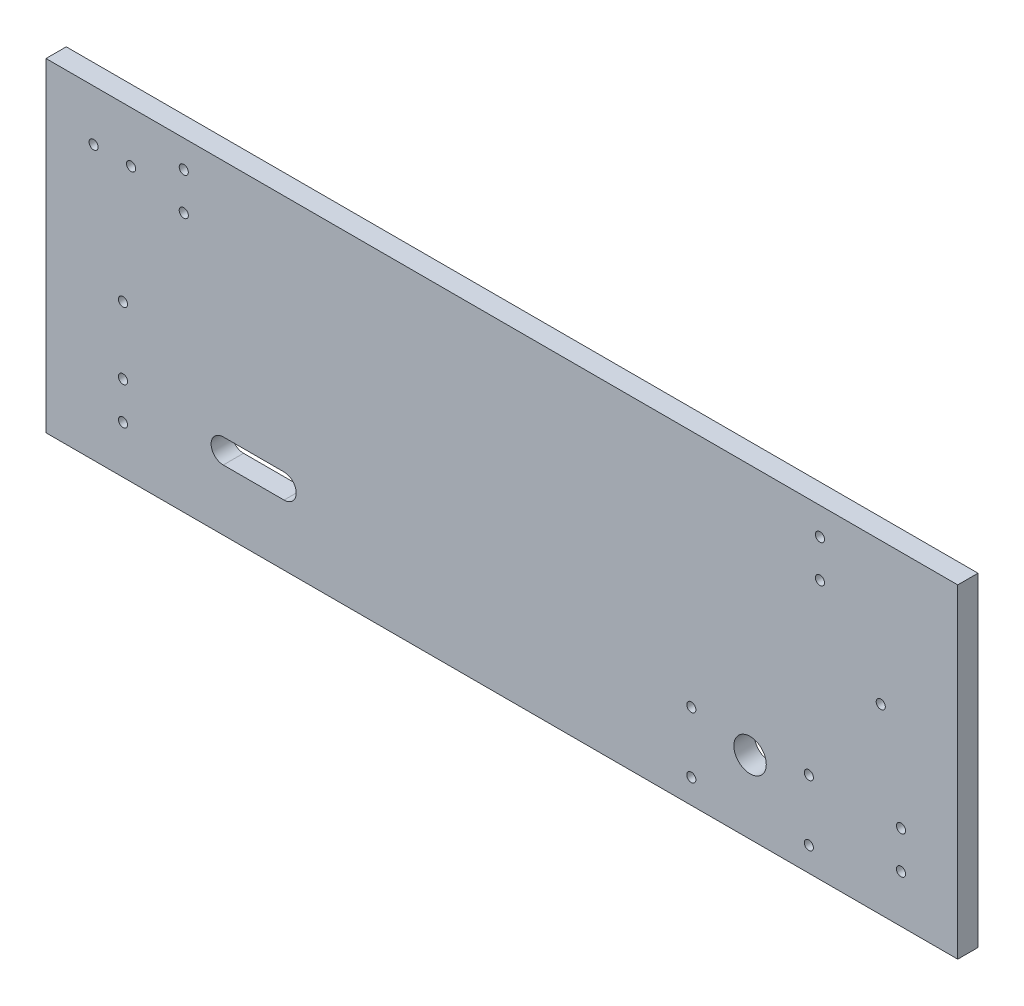
SolidWorks part; units mm, degrees
material "Pino"
ref_plane "Piano frontale" through (0, 0, 0) normal (0, 0, 1) x (1, 0, 0)
ref_plane "Piano superiore" through (0, 0, 0) normal (0, 1, 0) x (1, 0, 0)
ref_plane "Piano destro" through (0, 0, 0) normal (1, 0, 0) x (0, 0, -1)
sketch "Schizzo1" plane through (0, 0, 0) normal (0, 0, 1) x (1, 0, 0)
  line L1 (0, 0) -> (450, 0)
  line L2 (0, 0) -> (0, 160)
  line L3 (0, 160) -> (450, 160)
  line L4 (450, 0) -> (450, 160)
  dimension "D1" = 450
  dimension "D2" = 160
extrude "Estrusione-Estrusione1" add sketch "Schizzo1" along normal blind 10
sketch "Schizzo2" plane through (0, 0, 10) normal (0, 0, 1) x (1, 0, 0)
  line L0 (102.5, 36) -> (347.5, 36) construction
  line L1 (225, 0) -> (225, 36) construction
  line L2 (0, 0) -> (450, 0) construction
  line L3 (87.5, 36) -> (117.5, 36) construction
  line L4 (87.5, 42) -> (117.5, 42)
  line L5 (87.5, 30) -> (117.5, 30)
  line L7 (376.5, 42) -> (318.5, 42) construction
  line L8 (376.5, 42) -> (376.5, 12) construction
  line L9 (376.5, 12) -> (318.5, 12) construction
  line L10 (318.5, 42) -> (318.5, 12) construction
  circle A1 centre (347.5, 36) radius 8
  arc A2 (87.5, 42) -> (87.5, 30) centre (87.5, 36) ccw
  arc A3 (117.5, 30) -> (117.5, 42) centre (117.5, 36) ccw
  circle A4 centre (376.5, 42) radius 2.25
  circle A5 centre (376.5, 12) radius 2.25
  circle A6 centre (318.5, 12) radius 2.25
  circle A7 centre (318.5, 42) radius 2.25
  circle A8 centre (68, 146.5) radius 2.25
  circle A9 centre (68, 128) radius 2.25
  circle A10 centre (382, 146.5) radius 2.25
  circle A11 centre (382, 128) radius 2.25
  circle A12 centre (38, 42) radius 2.25
  circle A13 centre (38, 23.5) radius 2.25
  circle A14 centre (422, 42) radius 2.25
  circle A15 centre (422, 23.5) radius 2.25
  circle A16 centre (23.5, 134.9337) radius 2.25
  circle A17 centre (42, 134.9337) radius 2.25
  circle A18 centre (38, 75) radius 2.25
  circle A19 centre (412, 90) radius 2.25
  point P9 (102.5, 36)
  dimension "D2" = 16
  dimension "D3" = 12
  dimension "D5" = 30
  dimension "D6" = 29
  dimension "D10" = 4.5
  dimension "D17" = 4.5
  dimension "D18" = 4.5
  dimension "D1" = 36
  dimension "D4" = 245
  dimension "D7" = 29
  dimension "D8" = 6
  dimension "D9" = 30
extrude "Taglio-Estrusione1" cut sketch "Schizzo2" against normal blind 10
